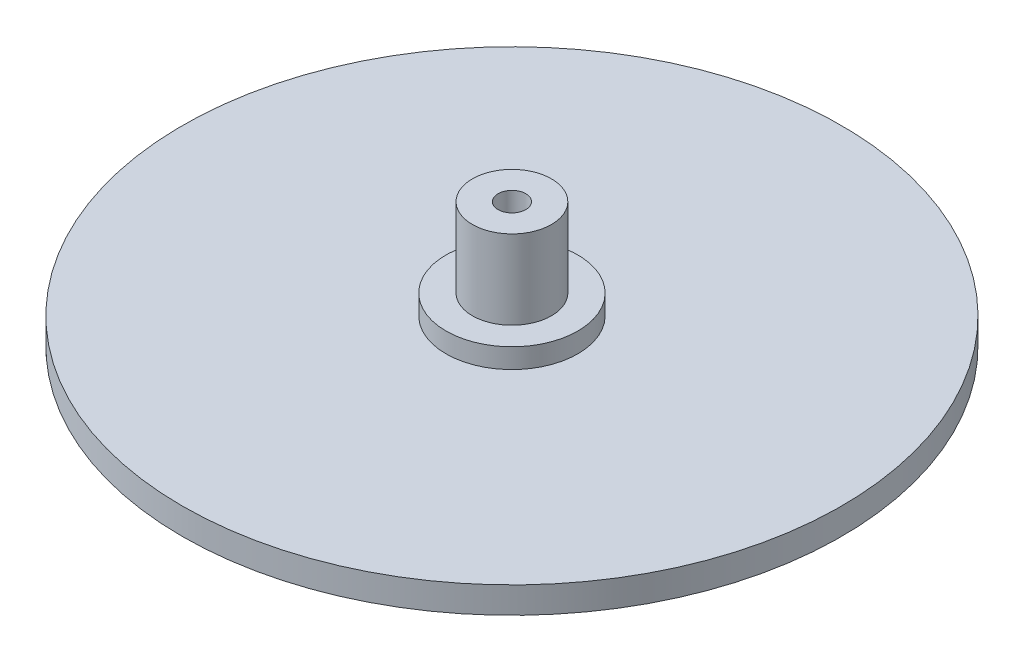
SolidWorks part; units mm, degrees
ref_plane "Front Plane" through (0, 0, 0) normal (0, 0, 1) x (1, 0, 0)
ref_plane "Top Plane" through (0, 0, 0) normal (0, 1, 0) x (1, 0, 0)
ref_plane "Right Plane" through (0, 0, 0) normal (1, 0, 0) x (0, 0, -1)
sketch "Sketch1" plane through (0, 0, 0) normal (0, 1, 0) x (1, 0, 0)
  circle A0 centre (0, 0) radius 25
  dimension "D1" = 50
extrude "Boss-Extrude1" add sketch "Sketch1" along normal blind 2 contours A0
sketch "Sketch2" plane through (0, 2, 0) normal (0, 1, 0) x (1, 0, 0)
  circle A0 centre (0, 0) radius 5
  dimension "D1" = 10
extrude "Boss-Extrude2" add sketch "Sketch2" along normal blind 1.5
sketch "Sketch3" plane through (0, 3.5, 0) normal (0, 1, 0) x (1, 0, 0)
  circle A0 centre (0, 0) radius 3
  dimension "D1" = 6
extrude "Boss-Extrude3" add sketch "Sketch3" along normal blind 6
sketch "Sketch4" plane through (0, 9.5, 0) normal (0, 1, 0) x (1, 0, 0)
  circle A0 centre (0, 0) radius 1.05
  dimension "D1" = 2.1
extrude "Cut-Extrude1" cut sketch "Sketch4" against normal blind 9
